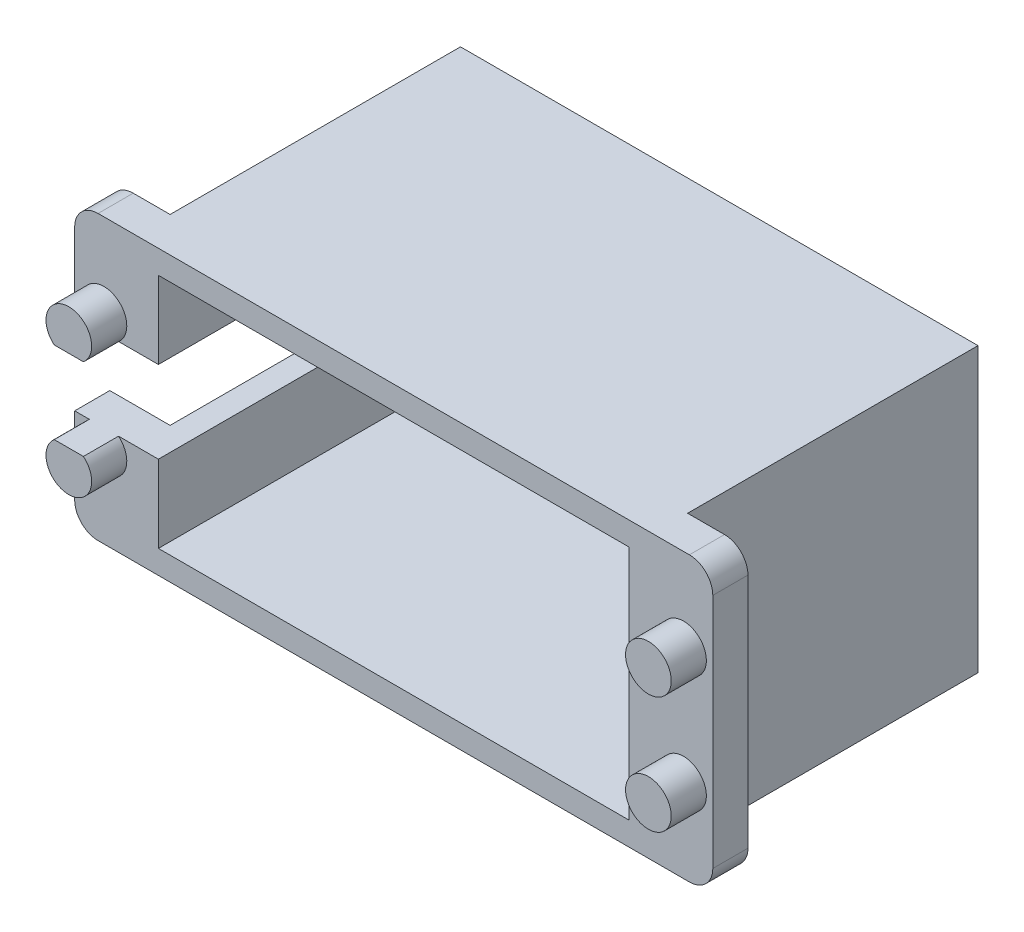
SolidWorks part; units mm, degrees
ref_plane "Plan de face" through (0, 0, 0) normal (0, 0, 1) x (1, 0, 0)
ref_plane "Plan de dessus" through (0, 0, 0) normal (0, 1, 0) x (1, 0, 0)
ref_plane "Plan de droite" through (0, 0, 0) normal (1, 0, 0) x (0, 0, -1)
sketch "Esquisse1" plane through (0, 0, 0) normal (0, 0, 1) x (1, 0, 0)
  line L0 (-2, 13.6) -> (0, 13.6)
  line L1 (0, 0) -> (40.2, 0)
  line L2 (0, 0) -> (0, 20.2)
  line L3 (0, 20.2) -> (40.2, 20.2)
  line L4 (40.2, 0) -> (40.2, 20.2)
  line L5 (-2, 22.2) -> (42.2, 22.2)
  line L6 (-2, 22.2) -> (-2, -2)
  line L7 (-2, -2) -> (42.2, -2)
  line L8 (42.2, 22.2) -> (42.2, -2)
  line L9 (0.1, 20.1) -> (40.1, 20.1) construction
  line L10 (0.1, 20.1) -> (0.1, 0.1) construction
  line L11 (0.1, 0.1) -> (40.1, 0.1) construction
  line L12 (40.1, 20.1) -> (40.1, 0.1) construction
  line L13 (-2, 6.6) -> (0, 6.6)
  line L14 (-1, 13.6) -> (-1, 6.6) construction
  point P19 (-1, 10.1)
  point P20 (-2, 10.1)
  dimension "D1" = 40.2
  dimension "D2" = 20.2
  dimension "D3" = 2
  dimension "D4" = 2
  dimension "D5" = 2
  dimension "D6" = 2
  dimension "D7" = 0.1
  dimension "D8" = 0.1
  dimension "D9" = 20
  dimension "D10" = 40
  dimension "D11" = 7
extrude "Boss.-Extru.1" add sketch "Esquisse1" along normal blind 27.8 contours L13 L6 L7 L8 L5 L0 L2 L3 L4 L1
sketch "Esquisse3" plane through (0, 0, 0) normal (0, 0, -1) x (-1, 0, 0)
  line L1 (0, 13.6) -> (2, 13.6)
  line L2 (0, 13.6) -> (0, 6.6)
  line L3 (0, 6.6) -> (2, 6.6)
  line L4 (2, 13.6) -> (2, 6.6)
extrude "Boss.-Extru.2" add sketch "Esquisse3" against normal blind 6.44
sketch "Esquisse5" plane through (0, 0, 27.8) normal (0, 0, 1) x (1, 0, 0)
  line L0 (20.1, 22.2) -> (20.1, -2) construction
  line L1 (-2, 22.2) -> (-5.15, 22.2)
  line L2 (-2, 22.2) -> (-2, -2)
  line L3 (-2, -2) -> (-5.15, -2)
  line L4 (-7.15, 20.2) -> (-7.15, 0)
  line L5 (-2, 22.2) -> (42.2, 22.2) construction
  line L6 (-2, -2) -> (42.2, -2) construction
  line L7 (47.35, 20.2) -> (47.35, 0)
  line L8 (42.2, -2) -> (45.35, -2)
  line L9 (42.2, 22.2) -> (42.2, -2)
  line L10 (42.2, 22.2) -> (45.35, 22.2)
  line L11 (-2, 13.6) -> (-7.15, 13.6)
  line L12 (-2, 6.6) -> (-7.15, 6.6)
  arc A1 (-5.15, -2) -> (-7.15, 0) centre (-5.15, 0) cw
  arc A2 (-5.15, 22.2) -> (-7.15, 20.2) centre (-5.15, 20.2) ccw
  arc A3 (45.35, 22.2) -> (47.35, 20.2) centre (45.35, 20.2) cw
  arc A4 (45.35, -2) -> (47.35, 0) centre (45.35, 0) ccw
  line M4 (-2, 6.6) -> (-2, -2)
  line M6 (42.2, -2) -> (42.2, 22.2)
  line M8 (-2, 22.2) -> (-2, 13.6)
  dimension "D1" = 2
extrude "Boss.-Extru.3" add sketch "Esquisse5" against normal blind 3 contours L1 A2 L4 L11 M8 | A1 L3 L12 L4 M4 | L8 A4 L7 A3 L10 M6
sketch "Esquisse7" plane through (0, 0, 27.8) normal (0, 0, 1) x (1, 0, 0)
  line L0 (0, 13.6) -> (0, 20.2) construction
  line L1 (-4.65, 15.1) -> (-4.65, 5.1) construction
  line L3 (20.1, 22.2) -> (20.1, -2) construction
  line L4 (-5.15, 22.2) -> (45.35, 22.2) construction
  line L5 (-5.15, -2) -> (45.35, -2) construction
  line L6 (44.85, 15.1) -> (44.85, 5.1) construction
  line L7 (-5.896, 13.6) -> (-3.404, 13.6)
  line L8 (-7.15, 13.6) -> (0, 13.6) construction
  line L9 (-5.896, 6.6) -> (-3.404, 6.6)
  line L10 (-7.15, 6.6) -> (0, 6.6) construction
  arc A0 (-3.404, 13.6) -> (-5.896, 13.6) centre (-4.65, 15.1) ccw
  arc A1 (-5.896, 6.6) -> (-3.404, 6.6) centre (-4.65, 5.1) ccw
  circle A2 centre (44.85, 5.1) radius 1.95
  circle A3 centre (44.85, 15.1) radius 1.95
  arc A4 (-5.896, 13.6) -> (-4.65, 13.15) centre (-4.65, 15.1) ccw construction
  arc A5 (-4.65, 13.15) -> (-3.404, 13.6) centre (-4.65, 15.1) ccw construction
  arc A6 (-4.65, 7.05) -> (-5.896, 6.6) centre (-4.65, 5.1) ccw construction
  arc A7 (-3.404, 6.6) -> (-4.65, 7.05) centre (-4.65, 5.1) ccw construction
  point P6 (-4.65, 10.1)
  point P7 (20.1, 10.1)
  dimension "D1" = 3.9
  dimension "D3" = 10
  dimension "D2" = 4.65
extrude "Boss.-Extru.4" add sketch "Esquisse7" along normal blind 3
